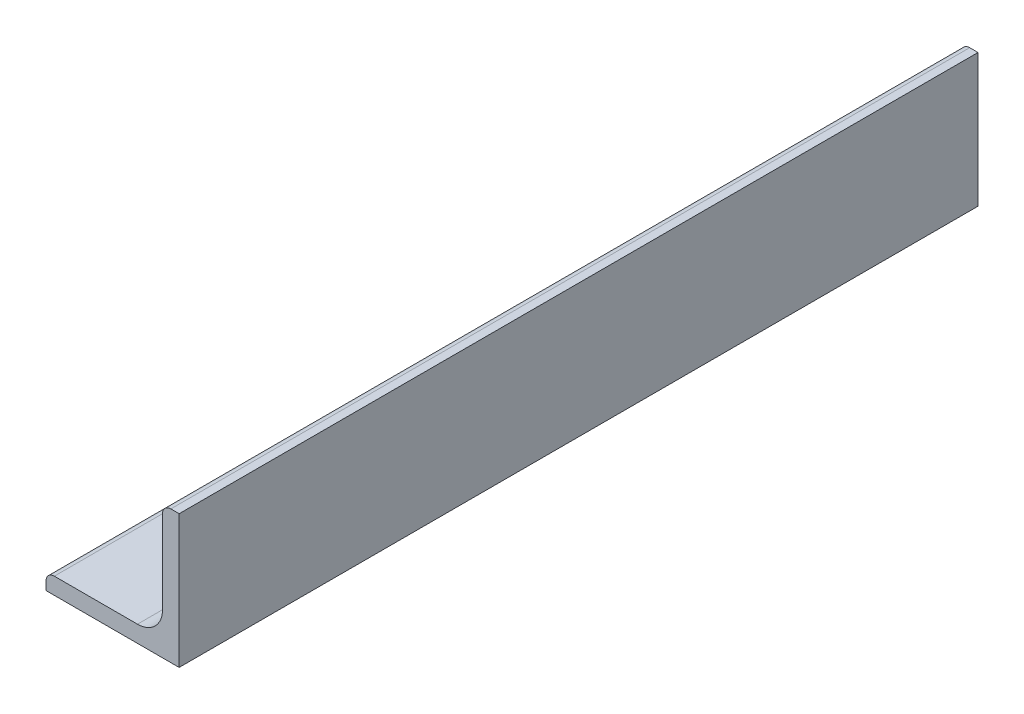
SolidWorks part; units mm, degrees
ref_plane "Front Plane" through (0, 0, 0) normal (0, 0, 1) x (1, 0, 0)
ref_plane "Top Plane" through (0, 0, 0) normal (0, 1, 0) x (1, 0, 0)
ref_plane "Right Plane" through (0, 0, 0) normal (1, 0, 0) x (0, 0, -1)
sketch "Sketch0" plane through (0, 0, 0) normal (0, 0, 1) x (1, 0, 0)
  line L0 (-12.7, -12.7) -> (12.7, -12.7)
  line L1 (12.7, -12.7) -> (12.7, 12.7)
  line L2 (12.7, 0) -> (0, 0) construction
  line L3 (0, 0) -> (0, -12.7) construction
  line L4 (9.525, -4.7498) -> (9.525, 12.7) construction
  line L5 (4.7498, -9.525) -> (-12.7, -9.525) construction
  arc A0 (9.525, -4.7498) -> (4.7498, -9.525) centre (4.7498, -4.7498) cw
  point P3 (8.1264, -8.1264)
  dimension "Inside Corner Radius" = 4.7752
  dimension "Outside Height" = 25.4
  dimension "Inside Height" = 22.225
  dimension "Inside Width" = 22.225
  dimension "Wall Thickness" = 3.175
  dimension "D1" = 3.175
  dimension "Outside Width" = 25.4
sketch "Sketch1" plane through (0, 0, 0) normal (1, 0, 0) x (0, 0, -1)
  line L0 (76.2, 0) -> (-76.2, 0)
  point P4 (0, 0)
  dimension "Length" = 152.4
sketch "Sketch2" plane through (0, 0, 0) normal (0, 0, 1) x (1, 0, 0)
  line L0 (-12.7, -12.7) -> (12.7, -12.7)
  line L1 (12.7, -12.7) -> (12.7, 12.7)
  line L2 (12.7, 12.7) -> (9.525, 12.7) construction
  line L3 (9.525, 11.1125) -> (9.525, -4.7498)
  line L4 (4.7498, -9.525) -> (-11.1125, -9.525)
  line L5 (-12.7, -12.7) -> (-12.7, -9.525) construction
  line L6 (11.1125, 12.7) -> (12.7, 12.7)
  line L7 (-12.7, -11.1125) -> (-12.7, -12.7)
  line L8 (12.7, 0) -> (0, 0) construction
  line L9 (0, 0) -> (0, -12.7) construction
  arc A0 (9.525, 11.1125) -> (11.1125, 12.7) centre (11.1125, 11.1125) cw
  arc A1 (-12.7, -11.1125) -> (-11.1125, -9.525) centre (-11.1125, -11.1125) cw
  arc A2 (9.525, -4.7498) -> (4.7498, -9.525) centre (4.7498, -4.7498) cw
  dimension "Inside Radius" = 4.7752
  dimension "Height" = 25.4
  dimension "Width" = 25.4
  dimension "Thickness" = 3.175
extrude "Boss-Extrude1" add sketch "Sketch2" along normal mid plane 152.4
sketch "Break Locations" plane through (0, 0, 0) normal (1, 0, 0) x (0, 0, -1)
  line L0 (-50.292, 0) -> (50.292, 0)
  line L1 (-76.2, -12.7) -> (-76.2, 12.7) construction
  line L2 (76.2, -12.7) -> (76.2, 12.7) construction
  point P0 (-54.61, 0)
  point P1 (54.61, 0)
  point P10 (0, 0)
  point P11 (50.292, 0)
  point P13 (-50.292, 0)
  dimension "D1" = 21.59
  dimension "D2" = 21.59
  dimension "D3" = 25.908
equation "\"D1@Break Locations\" = .85 * \"Height@Sketch2\""
equation "\"D2@Break Locations\"=\"D1@Break Locations\""
equation "\"Thickness@Sketch2\"=\"wall thickness@sketch0\""
equation "\"Height@Sketch2\"=\"outside height@sketch0\""
equation "\"Width@Sketch2\"=\"outside width@sketch0\""
equation "\"Inside Radius@Sketch2\"=\"inside corner radius@sketch0\""
equation "\"Length@Boss-Extrude1\"=\"length@sketch1\""
equation "\"D3@Break Locations\"=\"D2@Break Locations\"*1.2"
equation "\"D1@Sketch0\"=\"Wall Thickness@Sketch0\""
